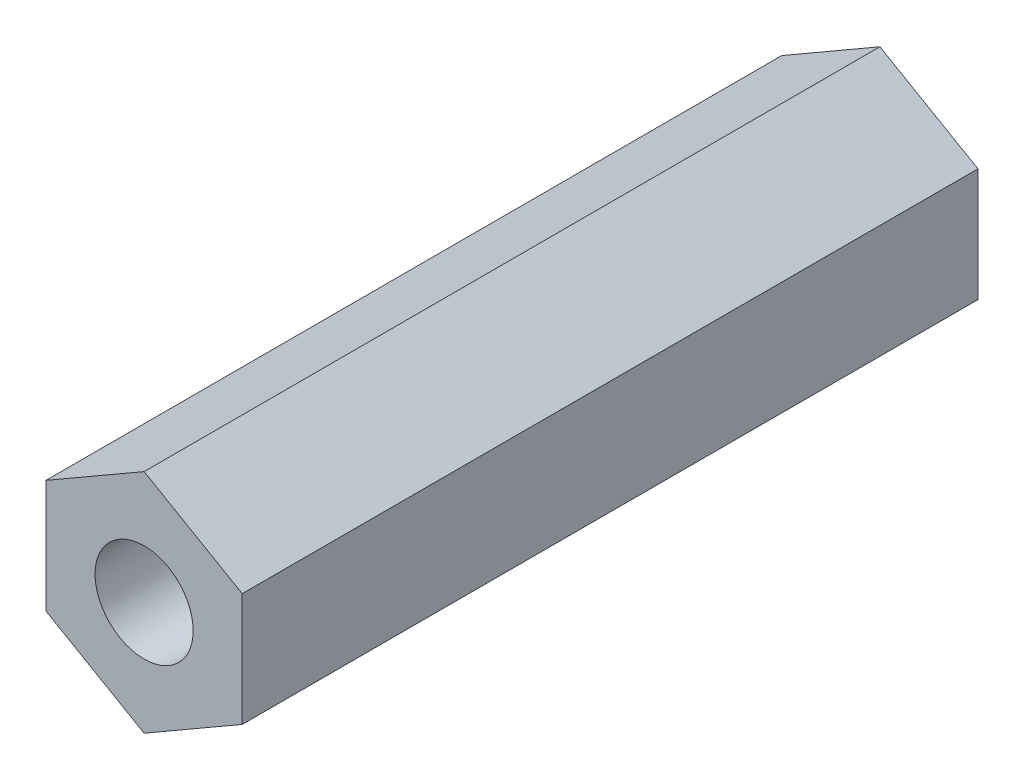
SolidWorks part; units mm, degrees
ref_plane "Front" through (0, 0, 0) normal (0, 0, 1) x (1, 0, 0)
ref_plane "Top" through (0, 0, 0) normal (0, 1, 0) x (1, 0, 0)
ref_plane "Right" through (0, 0, 0) normal (1, 0, 0) x (0, 0, -1)
sketch "Esquisse1" plane through (0, 0, 0) normal (0, 0, 1) x (1, 0, 0)
  line L1 (4, -2.3094) -> (4, 2.3094)
  line L2 (4, 2.3094) -> (0, 4.6188)
  line L3 (0, 4.6188) -> (-4, 2.3094)
  line L4 (-4, 2.3094) -> (-4, -2.3094)
  line L5 (-4, -2.3094) -> (0, -4.6188)
  line L6 (0, -4.6188) -> (4, -2.3094)
  circle A0 centre (0, 0) radius 2
  circle A1 centre (0, 0) radius 4 construction
  dimension "D1" = 4
  dimension "D2" = 8
extrude "Boss.-Extru.1" add sketch "Esquisse1" along normal blind 30
